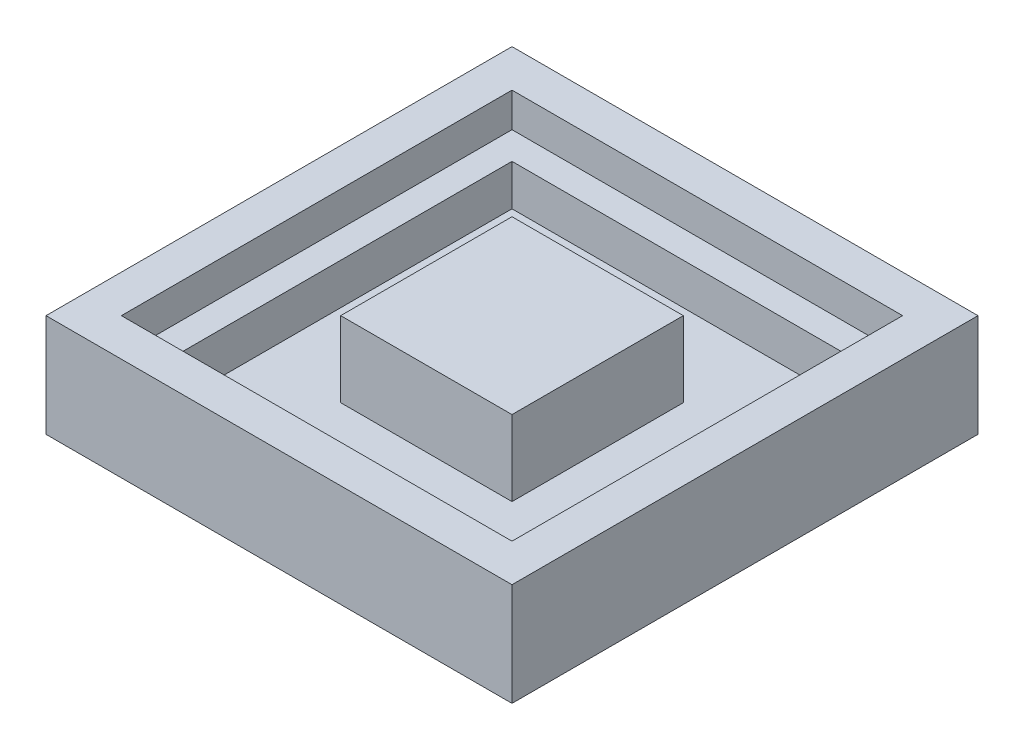
SolidWorks part; units mm, degrees
ref_plane "Спереди" through (0, 0, 0) normal (0, 0, 1) x (1, 0, 0)
ref_plane "Сверху" through (0, 0, 0) normal (0, 1, 0) x (1, 0, 0)
ref_plane "Справа" through (0, 0, 0) normal (1, 0, 0) x (0, 0, -1)
sketch "Эскиз1" plane through (0, 0, 0) normal (0, 1, 0) x (1, 0, 0)
  line L0 (0, 0) -> (34, 0)
  line L1 (0, 0) -> (0, 34)
  line L2 (34, 0) -> (34, 34)
  line L3 (0, 34) -> (34, 34)
  dimension "D1" = 34
extrude "Бобышка-Вытянуть1" add sketch "Эскиз1" along normal blind 8
sketch "Эскиз2" plane through (0, 8, 0) normal (0, 1, 0) x (1, 0, 0)
  line L0 (4.75, 4.75) -> (4.75, 29.25)
  line L1 (4.75, 4.75) -> (29.25, 4.75)
  line L2 (4.75, 29.25) -> (29.25, 29.25)
  line L3 (29.25, 4.75) -> (29.25, 29.25)
  line L4 (17, 34) -> (17, 0) construction
  line L6 (34, 34) -> (0, 34) construction
  line L7 (0, 0) -> (34, 0) construction
  line L8 (0, 17) -> (34, 17) construction
  line L9 (0, 34) -> (0, 0) construction
  line L10 (34, 0) -> (34, 34) construction
  point P16 (29.25, 17)
  point P17 (17, 29.25)
  dimension "D1" = 24.5
  dimension "D2" = 24.5
extrude "Вырез-Вытянуть1" cut sketch "Эскиз2" against normal blind 6
sketch "Эскиз3" plane through (0, 8, 0) normal (0, 1, 0) x (1, 0, 0)
  line L0 (2.75, 2.75) -> (2.75, 31.25)
  line L1 (2.75, 2.75) -> (31.25, 2.75)
  line L2 (2.75, 31.25) -> (31.25, 31.25)
  line L3 (31.25, 2.75) -> (31.25, 31.25)
  line L4 (4.75, 29.25) -> (4.75, 4.75) construction
  line L5 (4.75, 4.75) -> (29.25, 4.75) construction
  line L6 (29.25, 29.25) -> (4.75, 29.25) construction
  line L7 (29.25, 4.75) -> (29.25, 29.25) construction
  dimension "D1" = 2
  dimension "D2" = 2
  dimension "D3" = 2
  dimension "D4" = 2
extrude "Вырез-Вытянуть2" cut sketch "Эскиз3" against normal blind 3
sketch "Эскиз4" plane through (0, 2, 0) normal (0, 1, 0) x (1, 0, 0)
  line L0 (10.75, 23.25) -> (23.25, 23.25)
  line L1 (10.75, 23.25) -> (10.75, 10.75)
  line L2 (23.25, 23.25) -> (23.25, 10.75)
  line L3 (10.75, 10.75) -> (23.25, 10.75)
  line L4 (17, 29.25) -> (17, 4.75) construction
  line L5 (29.25, 29.25) -> (4.75, 29.25) construction
  line L6 (29.25, 17) -> (4.75, 17) construction
  line L7 (29.25, 4.75) -> (29.25, 29.25) construction
  line L8 (4.75, 29.25) -> (4.75, 4.75) construction
  line L9 (4.75, 4.75) -> (29.25, 4.75) construction
  point P12 (17, 23.25)
  point P17 (23.25, 17)
  dimension "D1" = 12.5
extrude "Бобышка-Вытянуть2" add sketch "Эскиз4" along normal up to surface (6 mm away) up to face at (17, 8, -17)
sketch "Эскиз5" plane through (0, 8, 0) normal (0, 1, 0) x (1, 0, 0)
  line L0 (31.25, 31.25) -> (2.75, 31.25) construction
  line L1 (31.25, 2.75) -> (31.25, 31.25) construction
  line L2 (2.75, 31.25) -> (2.75, 2.75) construction
  line L3 (10.75, 10.75) -> (23.25, 10.75) construction
  line L4 (0, 34) -> (0, 0)
  line L5 (0, 0) -> (34, 0)
  line L6 (34, 0) -> (34, 34)
  line L7 (34, 34) -> (0, 34)
  line L8 (0, 34) -> (0, 0)
  line L9 (0, 0) -> (34, 0)
  line L10 (34, 0) -> (34, 34)
  line L11 (34, 34) -> (0, 34)
  line L12 (2.75, 2.75) -> (31.25, 2.75) construction
  line L13 (31.25, 31.25) -> (2.75, 31.25)
  line L14 (31.25, 2.75) -> (31.25, 31.25)
  line L15 (2.75, 31.25) -> (2.75, 2.75)
  line L16 (10.75, 10.75) -> (23.25, 10.75)
  line L17 (2.75, 2.75) -> (31.25, 2.75)
  line L22 (10.75, 10.75) -> (23.25, 10.75)
  line L23 (23.25, 10.75) -> (23.25, 23.25)
  line L24 (23.25, 23.25) -> (10.75, 23.25)
  line L25 (10.75, 23.25) -> (10.75, 10.75)
  line L26 (10.75, 10.75) -> (23.25, 10.75)
  line L27 (23.25, 10.75) -> (23.25, 23.25)
  line L28 (23.25, 23.25) -> (10.75, 23.25)
  line L29 (10.75, 23.25) -> (10.75, 10.75)
  dimension "D1" = 0
  dimension "D2" = 0
extrude "Вырез-Вытянуть4" cut sketch "Эскиз5" against normal blind 0.5 contours L28 L29 L16 L27
